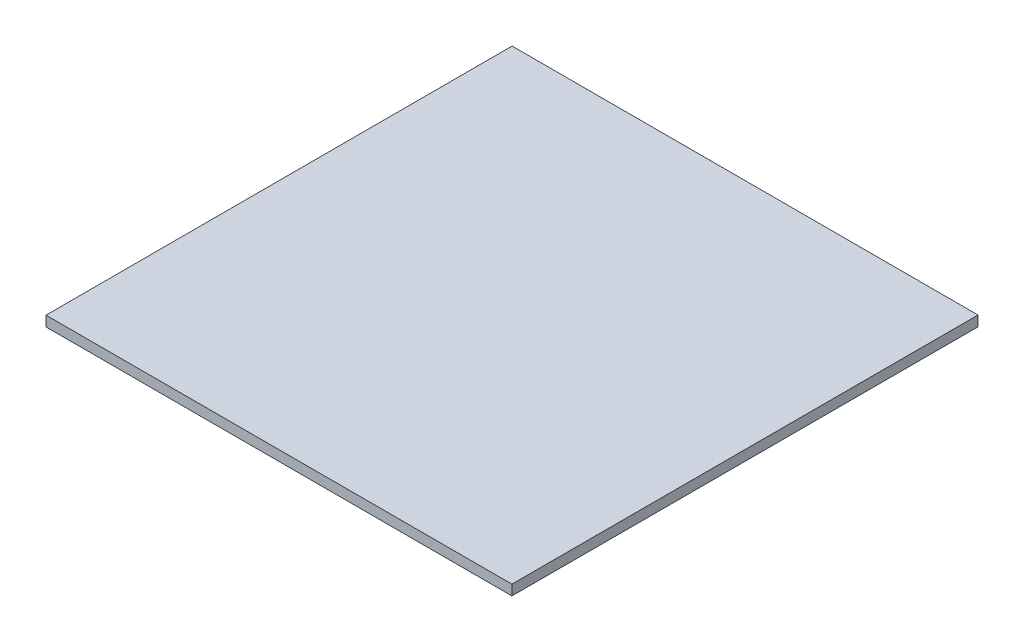
SolidWorks part; units mm, degrees
ref_plane "Front Plane" through (0, 0, 0) normal (0, 0, 1) x (1, 0, 0)
ref_plane "Top Plane" through (0, 0, 0) normal (0, 1, 0) x (1, 0, 0)
ref_plane "Right Plane" through (0, 0, 0) normal (1, 0, 0) x (0, 0, -1)
sketch "Sketch1" plane through (0, 0, 0) normal (0, 1, 0) x (1, 0, 0)
  line L1 (-29.3567, 258.0267) -> (260.1786, 258.0267)
  line L2 (-29.3567, 258.0267) -> (-29.3567, -31.6364)
  line L3 (-29.3567, -31.6364) -> (260.1786, -31.6364)
  line L4 (260.1786, 258.0267) -> (260.1786, -31.6364)
extrude "Boss-Extrude1" add sketch "Sketch1" along normal blind 6.3596 contours L2 L1 L4 L3
